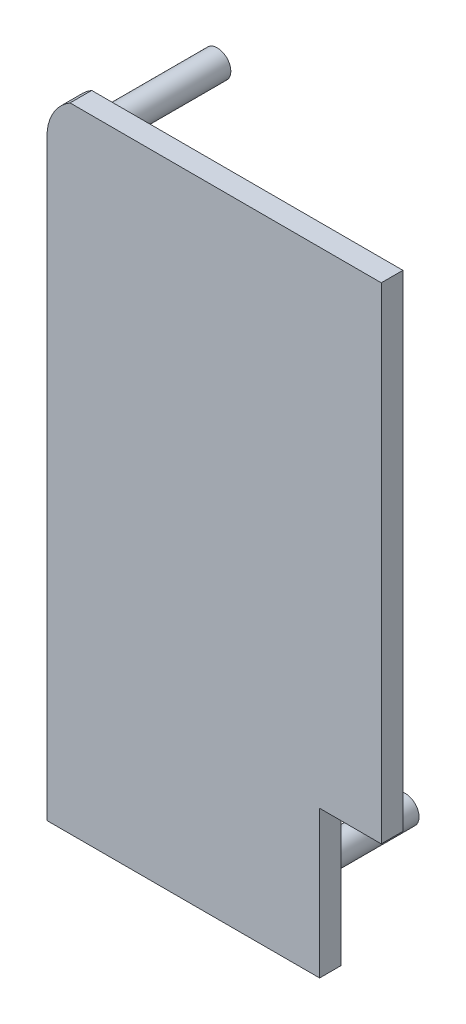
SolidWorks part; units mm, degrees
ref_plane "Front Plane" through (0, 0, 0) normal (0, 0, 1) x (1, 0, 0)
ref_plane "Top Plane" through (0, 0, 0) normal (0, 1, 0) x (1, 0, 0)
ref_plane "Right Plane" through (0, 0, 0) normal (1, 0, 0) x (0, 0, -1)
sketch "Sketch1" plane through (0, 0, 0) normal (0, 0, 1) x (1, 0, 0)
  line L0 (-41.3832, 43.4262) -> (-41.3832, 7.478)
  line L1 (-41.3832, 7.478) -> (-45.9435, 7.478)
  line L2 (-45.9435, 7.478) -> (-45.9435, -3.3961)
  line L3 (-45.9435, -3.3961) -> (-66.1131, -3.3961)
  line L4 (-66.1131, -3.3961) -> (-66.1131, 40.4405)
  line L5 (-41.3832, 43.4262) -> (-64.4067, 43.4405)
  arc A0 (-66.1131, 40.4405) -> (-64.4067, 43.4405) centre (-62.6229, 40.4405) cw
  line B0 (-27.6586, 1.8424) -> (-41.6586, 1.8424)
  line B1 (-67.4086, -6.4708) -> (-67.4086, 40.4405)
  line B2 (-17.6286, 6.8424) -> (-17.6286, 20.8424)
  line B3 (-12.6286, 20.8424) -> (-12.6286, 6.8424)
  line B4 (-12.6286, 6.8424) -> (1.3714, 6.8424)
  line B5 (10.3414, 1.8424) -> (-3.6586, 1.8424)
  line B6 (-64.4067, 43.4405) -> (89.8433, 43.3443)
  line B7 (92.8414, 40.3443) -> (92.8414, -31.6576)
  line B8 (89.8414, -34.6576) -> (30.9922, -34.6576)
  line B9 (30.6914, -34.6727) -> (-6.7085, -38.4425)
  line B10 (-7.0094, -38.4576) -> (-54.7463, -38.4576)
  line B11 (-57.5924, -36.4063) -> (-67.2546, -7.4194)
  line B12 (-38.6586, 25.8424) -> (-24.6586, 25.8424)
  line B13 (-24.6586, 25.8424) -> (-24.6586, 39.8424)
  line B14 (-24.6586, 39.8424) -> (-38.6586, 39.8424)
  line B15 (-38.6586, 39.8424) -> (-38.6586, 25.8424)
  line B16 (-19.6586, 25.8424) -> (-5.6586, 25.8424)
  line B17 (-5.6586, 25.8424) -> (-5.6586, 39.8424)
  line B18 (-5.6586, 39.8424) -> (-19.6586, 39.8424)
  line B19 (-19.6586, 39.8424) -> (-19.6586, 25.8424)
  line B20 (-0.6586, 25.8424) -> (13.3414, 25.8424)
  line B21 (13.3414, 25.8424) -> (13.3414, 39.8424)
  line B22 (13.3414, 39.8424) -> (-0.6586, 39.8424)
  line B23 (-0.6586, 39.8424) -> (-0.6586, 25.8424)
  line B24 (18.3414, 25.8424) -> (32.3414, 25.8424)
  line B25 (32.3414, 25.8424) -> (32.3414, 39.8424)
  line B26 (32.3414, 39.8424) -> (18.3414, 39.8424)
  line B27 (18.3414, 39.8424) -> (18.3414, 25.8424)
  line B28 (37.3414, 25.8424) -> (51.3414, 25.8424)
  line B29 (51.3414, 25.8424) -> (51.3414, 39.8424)
  line B30 (51.3414, 39.8424) -> (37.3414, 39.8424)
  line B31 (37.3414, 39.8424) -> (37.3414, 25.8424)
  line B32 (56.3414, 25.8424) -> (70.3414, 25.8424)
  line B33 (70.3414, 25.8424) -> (70.3414, 39.8424)
  line B34 (70.3414, 39.8424) -> (56.3414, 39.8424)
  line B35 (56.3414, 39.8424) -> (56.3414, 25.8424)
  line B36 (75.3414, 25.8424) -> (89.3414, 25.8424)
  line B37 (89.3414, 25.8424) -> (89.3414, 39.8424)
  line B38 (89.3414, 39.8424) -> (75.3414, 39.8424)
  line B39 (75.3414, 39.8424) -> (75.3414, 25.8424)
  line B40 (-31.6286, 6.8424) -> (-17.6286, 6.8424)
  line B41 (-17.6286, 20.8424) -> (-31.6286, 20.8424)
  line B42 (-31.6286, 20.8424) -> (-31.6286, 6.8424)
  line B43 (1.3714, 6.8424) -> (1.3714, 20.8424)
  line B44 (1.3714, 20.8424) -> (-12.6286, 20.8424)
  line B45 (6.3714, 6.8424) -> (20.3714, 6.8424)
  line B46 (20.3714, 6.8424) -> (20.3714, 20.8424)
  line B47 (20.3714, 20.8424) -> (6.3714, 20.8424)
  line B48 (6.3714, 20.8424) -> (6.3714, 6.8424)
  line B49 (25.3714, 6.8424) -> (39.3714, 6.8424)
  line B50 (39.3714, 6.8424) -> (39.3714, 20.8424)
  line B51 (39.3714, 20.8424) -> (25.3714, 20.8424)
  line B52 (25.3714, 20.8424) -> (25.3714, 6.8424)
  line B53 (44.3714, 6.8424) -> (58.3714, 6.8424)
  line B54 (58.3714, 6.8424) -> (58.3714, 20.8424)
  line B55 (58.3714, 20.8424) -> (44.3714, 20.8424)
  line B56 (44.3714, 20.8424) -> (44.3714, 6.8424)
  line B57 (68.1214, 6.8424) -> (82.1214, 6.8424)
  line B58 (82.1214, 6.8424) -> (82.1214, 20.8424)
  line B59 (82.1214, 20.8424) -> (68.1214, 20.8424)
  line B60 (68.1214, 20.8424) -> (68.1214, 6.8424)
  line B61 (-41.6586, -12.1576) -> (-27.6586, -12.1576)
  line B62 (-27.6586, -12.1576) -> (-27.6586, 1.8424)
  line B63 (-41.6586, 1.8424) -> (-41.6586, -12.1576)
  line B64 (-22.6586, -12.1576) -> (-8.6586, -12.1576)
  line B65 (-8.6586, -12.1576) -> (-8.6586, 1.8424)
  line B66 (-8.6586, 1.8424) -> (-22.6586, 1.8424)
  line B67 (-22.6586, 1.8424) -> (-22.6586, -12.1576)
  line B68 (-3.6586, -12.1576) -> (10.3414, -12.1576)
  line B69 (10.3414, -12.1576) -> (10.3414, 1.8424)
  line B70 (-3.6586, 1.8424) -> (-3.6586, -12.1576)
  line B71 (15.3414, -12.1576) -> (29.3414, -12.1576)
  line B72 (29.3414, -12.1576) -> (29.3414, 1.8424)
  line B73 (29.3414, 1.8424) -> (15.3414, 1.8424)
  line B74 (15.3414, 1.8424) -> (15.3414, -12.1576)
  line B75 (34.3414, -12.1576) -> (48.3414, -12.1576)
  line B76 (48.3414, -12.1576) -> (48.3414, 1.8424)
  line B77 (48.3414, 1.8424) -> (34.3414, 1.8424)
  line B78 (34.3414, 1.8424) -> (34.3414, -12.1576)
  line B79 (53.3414, -12.1576) -> (67.3414, -12.1576)
  line B80 (67.3414, -12.1576) -> (67.3414, 1.8424)
  line B81 (67.3414, 1.8424) -> (53.3414, 1.8424)
  line B82 (53.3414, 1.8424) -> (53.3414, -12.1576)
  line B83 (72.3414, -12.1576) -> (86.3414, -12.1576)
  line B84 (86.3414, -12.1576) -> (86.3414, 1.8424)
  line B85 (86.3414, 1.8424) -> (72.3414, 1.8424)
  line B86 (72.3414, 1.8424) -> (72.3414, -12.1576)
  line B87 (34.3414, -31.1576) -> (48.3414, -31.1576)
  line B88 (48.3414, -31.1576) -> (48.3414, -17.1576)
  line B89 (48.3414, -17.1576) -> (34.3414, -17.1576)
  line B90 (34.3414, -17.1576) -> (34.3414, -31.1576)
  line B91 (53.3414, -31.1576) -> (67.3414, -31.1576)
  line B92 (67.3414, -31.1576) -> (67.3414, -17.1576)
  line B93 (67.3414, -17.1576) -> (53.3414, -17.1576)
  line B94 (53.3414, -17.1576) -> (53.3414, -31.1576)
  line B95 (72.3414, -31.1576) -> (86.3414, -31.1576)
  line B96 (86.3414, -31.1576) -> (86.3414, -17.1576)
  line B97 (86.3414, -17.1576) -> (72.3414, -17.1576)
  line B98 (72.3414, -17.1576) -> (72.3414, -31.1576)
  line B99 (-48.6586, -34.9576) -> (-34.6586, -34.9576)
  line B100 (-34.6586, -34.9576) -> (-34.6586, -20.9576)
  line B101 (-34.6586, -20.9576) -> (-48.6586, -20.9576)
  line B102 (-48.6586, -20.9576) -> (-48.6586, -34.9576)
  line B103 (-20.1586, -34.9576) -> (-6.1586, -34.9576)
  line B104 (-6.1586, -34.9576) -> (-6.1586, -20.9576)
  line B105 (-6.1586, -20.9576) -> (-20.1586, -20.9576)
  line B106 (-20.1586, -20.9576) -> (-20.1586, -34.9576)
  arc B107 (92.8414, 40.3443) -> (89.8433, 43.3443) centre (89.8414, 40.3443) ccw
  arc B108 (89.8414, -34.6576) -> (92.8414, -31.6576) centre (89.8414, -31.6576) ccw
  arc B109 (30.9922, -34.6576) -> (30.6914, -34.6727) centre (30.9922, -37.6576) ccw
  arc B110 (-7.0094, -38.4576) -> (-6.7085, -38.4425) centre (-7.0094, -35.4576) ccw
  arc B111 (-57.5924, -36.4063) -> (-54.7463, -38.4576) centre (-54.7463, -35.4576) ccw
  arc B112 (-67.4086, -6.4708) -> (-67.2546, -7.4194) centre (-64.4086, -6.4708) ccw
  arc B113 (-64.4067, 43.4405) -> (-67.4086, 40.4405) centre (-64.4086, 40.4405) ccw
  line B114 (-72.138, -6.7459) -> (-72.138, 40.1654)
  line B115 (-69.138, -6.7459) -> (-69.138, 40.1654)
  line B116 (-64.133, 48.1654) -> (90.117, 48.0691)
  line B117 (98.112, 40.0691) -> (98.112, -31.9327)
  line B118 (90.112, -39.9327) -> (31.3633, -39.9327)
  line B119 (31.3633, -39.9327) -> (-5.9365, -43.6924)
  line B120 (-6.7388, -43.7327) -> (-54.4758, -43.7327)
  line B121 (-62.0652, -38.2626) -> (-71.7275, -9.2757)
  line B122 (-64.1349, 45.1654) -> (90.1151, 45.0691)
  line B123 (95.112, 40.0691) -> (95.112, -31.9327)
  line B124 (90.112, -36.9327) -> (31.2628, -36.9327)
  line B125 (31.1625, -36.9378) -> (-6.2374, -40.7075)
  line B126 (-6.7388, -40.7327) -> (-54.4758, -40.7327)
  line B127 (-59.2192, -37.3139) -> (-68.8814, -8.327)
  arc B128 (98.112, 40.0691) -> (90.117, 48.0691) centre (90.112, 40.0691) ccw
  arc B129 (90.112, -39.9327) -> (98.112, -31.9327) centre (90.112, -31.9327) ccw
  arc B130 (-6.7388, -43.7327) -> (-5.9365, -43.6924) centre (-6.7388, -35.7327) ccw
  arc B131 (-62.0652, -38.2626) -> (-54.4758, -43.7327) centre (-54.4758, -35.7327) ccw
  arc B132 (-72.138, -6.7459) -> (-71.7275, -9.2757) centre (-64.138, -6.7459) ccw
  arc B133 (-64.133, 48.1654) -> (-72.138, 40.1654) centre (-64.138, 40.1654) ccw
  arc B134 (95.112, 40.0691) -> (90.1151, 45.0691) centre (90.112, 40.0691) ccw
  arc B135 (90.112, -36.9327) -> (95.112, -31.9327) centre (90.112, -31.9327) ccw
  arc B136 (31.2628, -36.9327) -> (31.1625, -36.9378) centre (31.2628, -37.9327) ccw
  arc B137 (-6.7388, -40.7327) -> (-6.2374, -40.7075) centre (-6.7388, -35.7327) ccw
  arc B138 (-59.2192, -37.3139) -> (-54.4758, -40.7327) centre (-54.4758, -35.7327) ccw
  arc B139 (-69.138, -6.7459) -> (-68.8814, -8.327) centre (-64.138, -6.7459) ccw
  arc B140 (-64.1349, 45.1654) -> (-69.138, 40.1654) centre (-64.138, 40.1654) ccw
sketch_block_instance "switch_plate (2)-1"
sketch_block "switch_plate (2)"
sketch_block_instance "wall_outline (2)-1"
sketch_block "wall_outline (2)"
extrude "Boss-Extrude1" add sketch "Sketch1" along normal blind 1.6 contours L3 L4 A0 L5 L0 L1 L2
sketch "Sketch3" plane through (0, 0, 0) normal (0, 0, -1) x (-1, 0, 0)
  circle A0 centre (50.189, 0) radius 1
  circle A1 centre (60.9289, 0) radius 1
  circle A2 centre (64.1134, 40.8152) radius 1
extrude "Boss-Extrude2" add sketch "Sketch3" along normal blind 9
